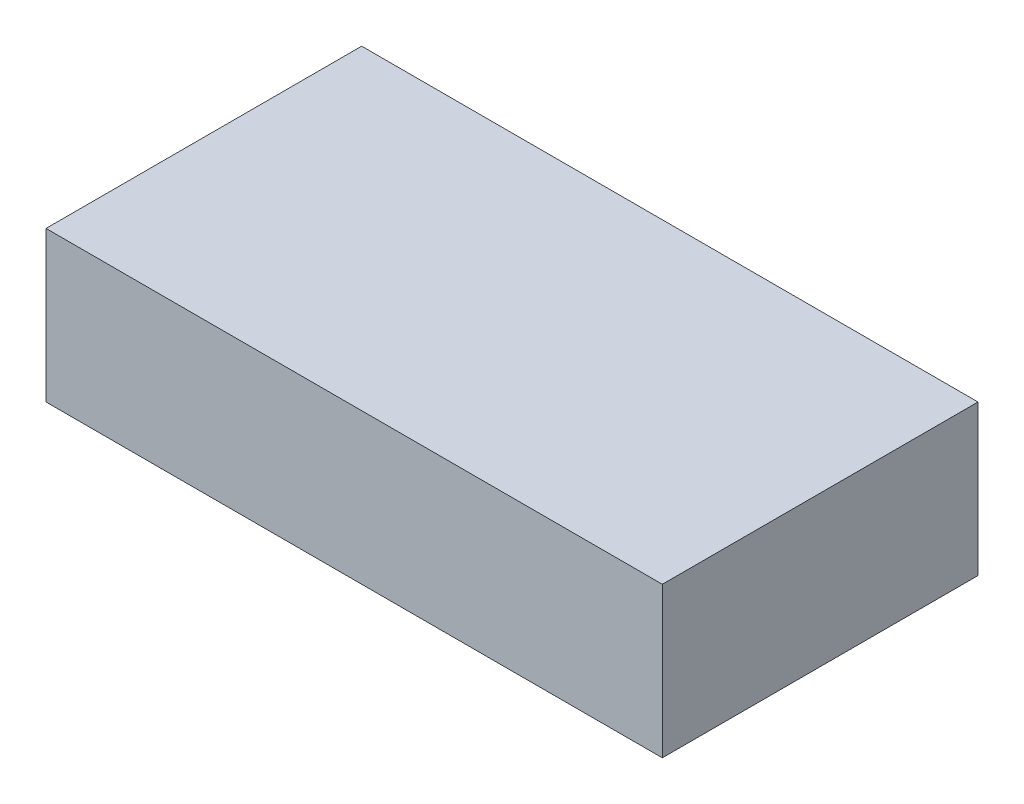
SolidWorks part; units mm, degrees
ref_plane "Front" through (0, 0, 0) normal (0, 0, 1) x (1, 0, 0)
ref_plane "Top" through (0, 0, 0) normal (0, 1, 0) x (1, 0, 0)
ref_plane "Right" through (0, 0, 0) normal (1, 0, 0) x (0, 0, -1)
sketch "Sketch1" plane through (0, 0, 0) normal (0, 1, 0) x (1, 0, 0)
  line L1 (0, 0) -> (41, 0)
  line L2 (0, 0) -> (0, 21)
  line L3 (0, 21) -> (41, 21)
  line L4 (41, 0) -> (41, 21)
  dimension "D1" = 41
  dimension "D2" = 21
extrude "Boss-Extrude1" add sketch "Sketch1" along normal blind 10
